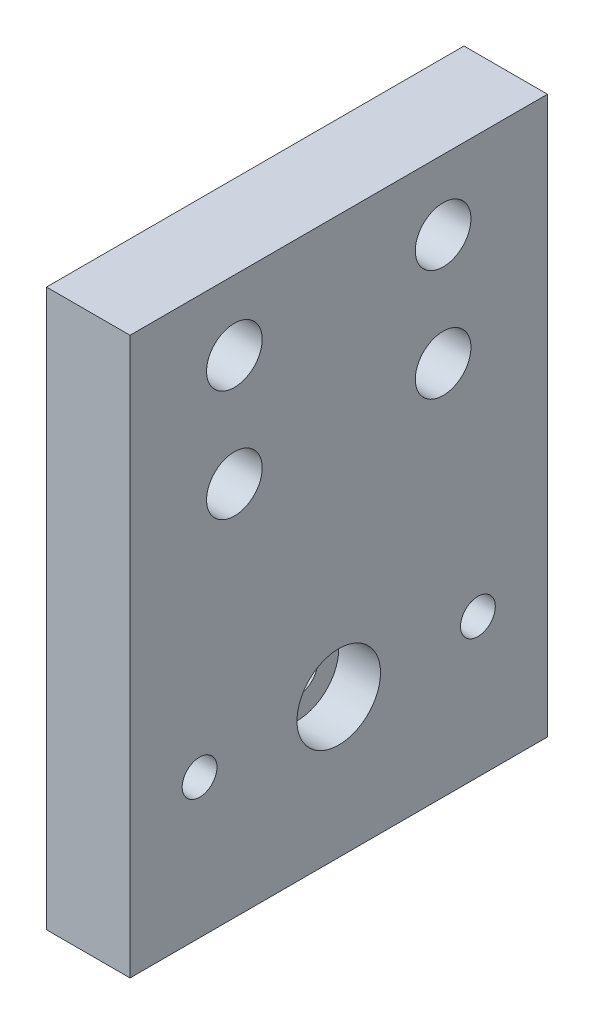
SolidWorks part; units mm, degrees
ref_plane "Front Plane" through (0, 0, 0) normal (0, 0, 1) x (1, 0, 0)
ref_plane "Top Plane" through (0, 0, 0) normal (0, 1, 0) x (1, 0, 0)
ref_plane "Right Plane" through (0, 0, 0) normal (1, 0, 0) x (0, 0, -1)
sketch "Sketch2" plane through (0, 0, 0) normal (1, 0, 0) x (0, 0, -1)
  line L1 (0, 0) -> (-150, 0)
  line L2 (0, 0) -> (0, 200)
  line L3 (0, 200) -> (-150, 200)
  line L4 (-150, 0) -> (-150, 200)
  dimension "D1" = 200
extrude "Boss-Extrude1" add sketch "Sketch2" along normal blind 30
sketch "Sketch3" plane through (30, 0, 0) normal (1, 0, 0) x (0, 0, -1)
  line L0 (-150, 200) -> (0, 200) construction
  line L1 (-150, 200) -> (-150, 0) construction
  line L2 (-150, 200) -> (-150, 0) construction
  line L3 (-75, 200) -> (-75, 0) construction
  line L4 (-150, 0) -> (0, 0) construction
  circle A0 centre (-112.5, 175) radius 10
  circle A1 centre (-37.5, 175) radius 10
  circle A2 centre (-112.5, 135) radius 10
  circle A3 centre (-37.5, 135) radius 10
  dimension "D1" = 40
  dimension "D2" = 20
  dimension "D3" = 20
extrude "Cut-Extrude1" cut sketch "Sketch3" against normal blind 30
sketch "Sketch4" plane through (30, 0, 0) normal (1, 0, 0) x (0, 0, -1)
  line L0 (-75, 200) -> (-75, 0) construction
  line L1 (0, 200) -> (-150, 200) construction
  line L2 (-150, 0) -> (0, 0) construction
  circle A0 centre (-75, 50) radius 15
  dimension "D1" = 30
  dimension "D2" = 50
extrude "Cut-Extrude2" cut sketch "Sketch4" against normal blind 15
sketch "Sketch6" plane through (30, 0, 0) normal (1, 0, 0) x (0, 0, -1)
  circle A0 centre (-75, 50) radius 7.5
  dimension "D1" = 15
extrude "Cut-Extrude3" cut sketch "Sketch6" against normal blind 30
sketch "Sketch7" plane through (30, 0, 0) normal (1, 0, 0) x (0, 0, -1)
  line L0 (-75, 50) -> (-125, 50) construction
  line L1 (-125, 50) -> (-25, 50) construction
  line L2 (0, 0) -> (0, 200) construction
  line L3 (-150, 200) -> (-150, 0) construction
  circle A0 centre (-125, 50) radius 4.5
  circle A1 centre (-25, 50) radius 4.5
  dimension "D1" = 9
  dimension "D2" = 9
  dimension "D3" = 25
  dimension "D4" = 25
extrude "Cut-Extrude4" cut sketch "Sketch7" against normal blind 30
sketch "Sketch8" plane through (0, 0, 0) normal (1, 0, 0) x (0, 0, -1)
  circle A0 centre (-25, 50) radius 6.25
  circle A1 centre (-125, 50) radius 5
  circle A2 centre (-125, 50) radius 6.25
  dimension "D1" = 10
  dimension "D2" = 12.5
  dimension "D3" = 12.5
sketch "Sketch9" plane through (30, 0, 0) normal (1, 0, 0) x (0, 0, -1)
  circle A0 centre (-125, 50) radius 6.25
  circle A1 centre (-25, 50) radius 6.25
  dimension "D1" = 12.5
  dimension "D2" = 12.5
extrude "Cut-Extrude6" cut sketch "Sketch9" against normal blind 9
